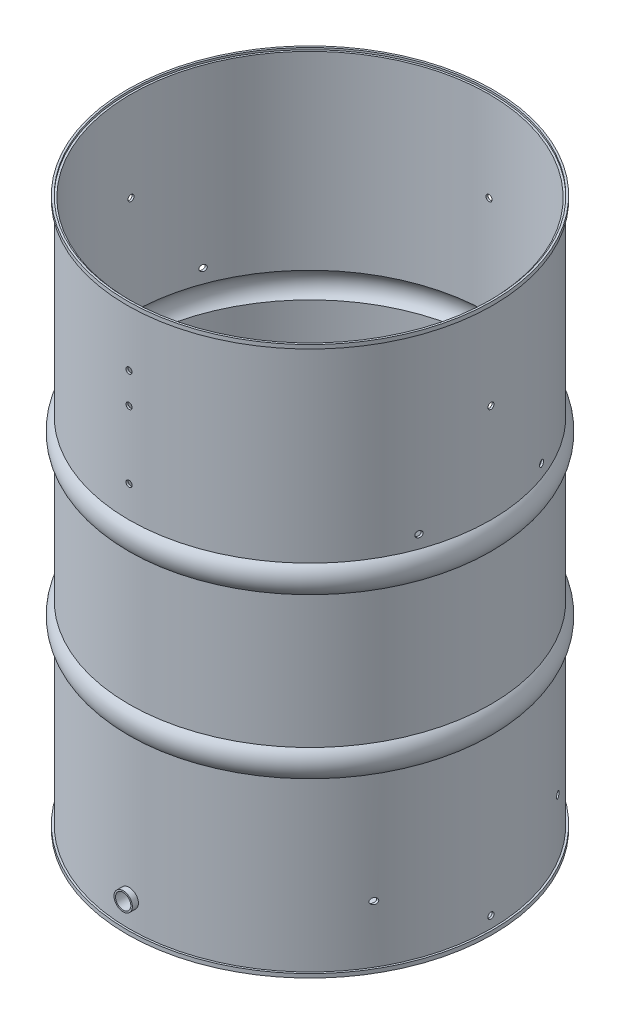
SolidWorks part; units mm, degrees
material "Plain Carbon Steel"
ref_plane "Front Plane" through (0, 0, 0) normal (0, 0, 1) x (1, 0, 0)
ref_plane "Top Plane" through (0, 0, 0) normal (0, 1, 0) x (1, 0, 0)
ref_plane "Right Plane" through (0, 0, 0) normal (1, 0, 0) x (0, 0, -1)
sketch "Sketch1" plane through (0, 0, 0) normal (0, 0, 1) x (1, 0, 0)
  line L0 (292.1, 206.5654) -> (0, 206.5654)
  line L1 (0, 206.5654) -> (0, 203.3904)
  line L2 (0, 203.3904) -> (298.45, 203.3904)
  line L3 (298.45, 203.3904) -> (298.45, 209.7404)
  line L4 (298.45, 209.7404) -> (295.275, 209.7404)
  line L5 (295.275, 209.7404) -> (295.275, 482.7904)
  line L6 (295.275, 526.9283) -> (295.275, 742.8283)
  line L7 (295.275, 787.3861) -> (295.275, 1092.1861)
  line L8 (295.275, 1092.1861) -> (298.45, 1092.1861)
  line L9 (298.45, 1092.1861) -> (298.45, 1098.5361)
  line L10 (298.45, 1098.5361) -> (295.275, 1098.5361)
  line L11 (295.275, 1098.5361) -> (295.275, 1095.3611)
  line L12 (295.275, 1095.3611) -> (292.1, 1095.3611)
  line L13 (292.1, 1095.3611) -> (292.1, 786.0297)
  line L14 (292.1, 744.1847) -> (292.1, 525.5714)
  line L15 (292.1, 484.1473) -> (292.1, 206.5654)
  line L16 (0, 1098.5361) -> (0, 203.3904) construction
  arc A0 (295.275, 526.9283) -> (295.275, 482.7904) centre (273.2061, 504.8594) cw
  arc A1 (295.275, 787.3861) -> (295.275, 742.8283) centre (272.9961, 765.1072) cw
  arc A2 (292.1, 786.0297) -> (292.1, 744.1847) centre (272.9961, 765.1072) cw
  arc A3 (292.1, 525.5714) -> (292.1, 484.1473) centre (273.2061, 504.8594) cw
revolve "Revolve1" add sketch "Sketch1" angle 360 about L16
sketch "Sketch2" plane through (0, 0, 0) normal (0, 0, 1) x (1, 0, 0)
  line L0 (-298.45, 203.3904) -> (298.45, 203.3904) construction
  circle A0 centre (0, 253.3904) radius 15
  dimension "D1" = 30
  dimension "D2" = 50
extrude "Boss-Extrude1" add sketch "Sketch2" along normal blind 304.8
sketch "Sketch4" plane through (0, 0, 304.8) normal (0, 0, 1) x (1, 0, 0)
  circle A0 centre (0, 253.3904) radius 12.5
  dimension "D1" = 25
extrude "Air Inlet Hole" cut sketch "Sketch4" against normal blind 303.464
sketch "Sketch5" plane through (0, 206.5654, 0) normal (0, 1, 0) x (1, 0, 0)
  circle A0 centre (0, 0) radius 253.0212
extrude "Sweep Cut for Air Inlet" cut sketch "Sketch5" along normal blind 76.2
sketch "Sketch6" plane through (0, 0, 0) normal (0, 0, 1) x (1, 0, 0)
  line L0 (295.275, 742.8283) -> (-295.275, 742.8283) construction
  circle A0 centre (0, 628.5283) radius 75
  dimension "D1" = 150
  dimension "D2" = 114.3
extrude "Coal Shute Hole" cut sketch "Sketch6" against normal through all
sketch "Sketch7" plane through (0, 0, 0) normal (1, 0, 0) x (0, 0, -1)
  line L0 (295.275, 1098.5361) -> (-295.275, 1098.5361) construction
  line L1 (298.45, 1098.5361) -> (-298.45, 1098.5361) construction
  circle A0 centre (-99.9987, 808.5361) radius 5
  circle A1 centre (100.0013, 808.5361) radius 5
  point P0 (100.0013, 808.5361)
  point P1 (-99.9987, 808.5361)
  point P2 (0, 809.0507)
  dimension "D3" = 10
  dimension "D4" = 10
  dimension "D1" = 200
  dimension "D2" = 100
  dimension "D5" = 290
  dimension "D6" = 290
extrude "Water Pan Holes" cut sketch "Sketch7" against normal through all and the other way through all
sketch "Sketch8" plane through (0, 0, 0) normal (1, 0, 0) x (0, 0, -1)
  line L0 (295.275, 1098.5361) -> (-295.275, 1098.5361) construction
  circle A0 centre (0, 948.5361) radius 5
  point P0 (0, 948.5361)
  dimension "D1" = 10
  dimension "D2" = 150
extrude "Grill Hole 1" cut sketch "Sketch8" against normal through all and the other way through all
sketch "Sketch9" plane through (0, 0, 0) normal (0, 0, 1) x (1, 0, 0)
  line L0 (295.275, 1098.5361) -> (-295.275, 1098.5361) construction
  circle A0 centre (0, 948.5361) radius 5
  dimension "D1" = 10
  dimension "D2" = 150
extrude "Grill Hole 2" cut sketch "Sketch9" against normal through all and the other way through all
sketch "Sketch10" plane through (0, 0, 0) normal (1, 0, 0) x (0, 0, -1)
  line L2 (-298.45, 203.3904) -> (298.45, 203.3904) construction
  circle A0 centre (150, 303.3904) radius 5
  circle A1 centre (-150, 303.3904) radius 5
  point P0 (0, 303.3904)
  dimension "D1" = 10
  dimension "D2" = 10
  dimension "D3" = 150
  dimension "D4" = 150
  dimension "D5" = 100
extrude "Coal Basket Holes" cut sketch "Sketch10" against normal through all and the other way through all
sketch "Sketch11" plane through (0, 0, 0) normal (1, 0, 0) x (0, 0, -1)
  line L0 (-298.45, 203.3904) -> (298.45, 203.3904) construction
  circle A0 centre (0, 228.3904) radius 5
  dimension "D1" = 10
  dimension "D2" = 25
extrude "Air Spreader Hole" cut sketch "Sketch11" against normal through all and the other way through all
sketch "Sketch12" plane through (0, 0, 0) normal (0, 0, 1) x (1, 0, 0)
  line L0 (298.45, 1098.5361) -> (-298.45, 1098.5361) construction
  circle A0 centre (0, 838.5361) radius 5
  circle A1 centre (0, 998.5361) radius 5
  dimension "D1" = 10
  dimension "D2" = 10
  dimension "D3" = 160
  dimension "D4" = 100
extrude "Bracket Holes" cut sketch "Sketch12" along normal through all
